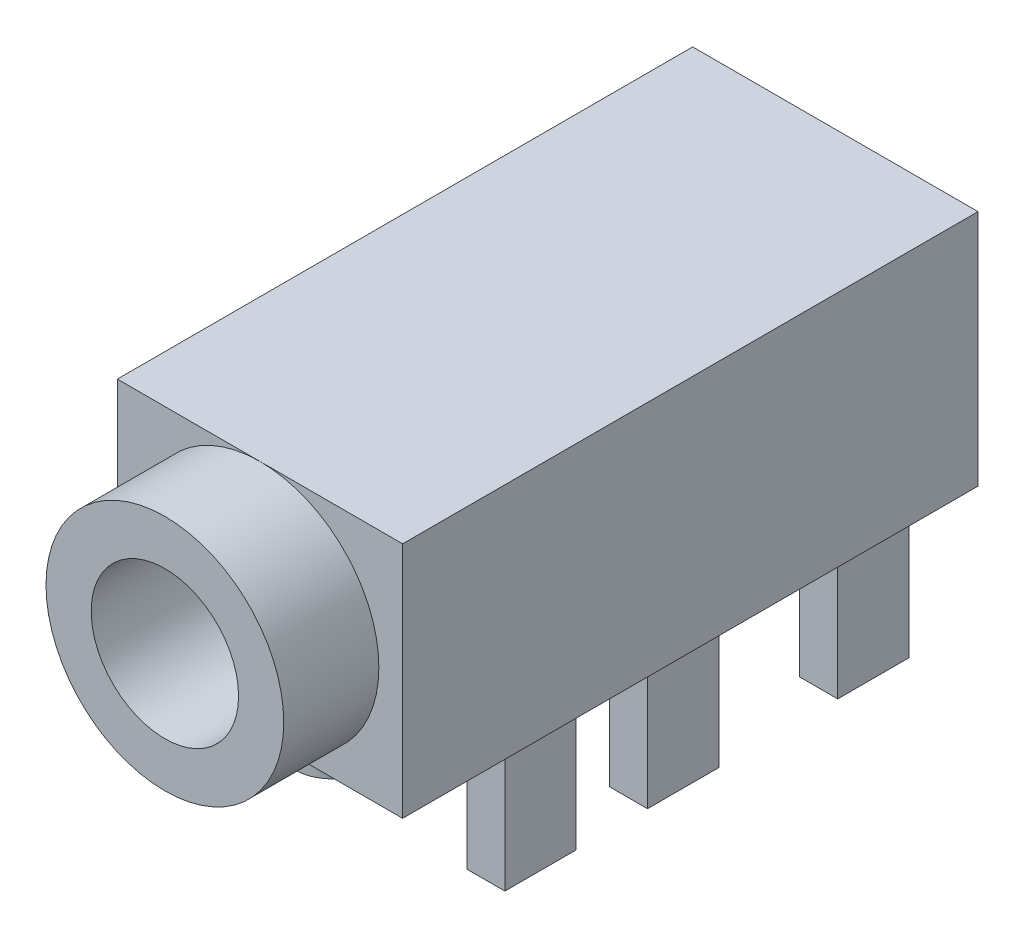
SolidWorks part; units mm, degrees
ref_plane "Front Plane" through (0, 0, 0) normal (0, 0, 1) x (1, 0, 0)
ref_plane "Top Plane" through (0, 0, 0) normal (0, 1, 0) x (1, 0, 0)
ref_plane "Right Plane" through (0, 0, 0) normal (1, 0, 0) x (0, 0, -1)
sketch "Sketch1" plane through (0, 0, 0) normal (0, 1, 0) x (1, 0, 0)
  line L1 (-3, 6.05) -> (3, 6.05)
  line L2 (-3, 6.05) -> (-3, -6.05)
  line L3 (-3, -6.05) -> (3, -6.05)
  line L4 (3, 6.05) -> (3, -6.05)
  line L5 (-3, 6.05) -> (3, -6.05) construction
  line L6 (-3, -6.05) -> (3, 6.05) construction
  point P0 (0, 0)
  dimension "D1" = 12.1
  dimension "D2" = 6
extrude "Boss-Extrude1" add sketch "Sketch1" along normal blind 5
sketch "Sketch2" plane through (0, 0, 6.05) normal (0, 0, 1) x (1, 0, 0)
  line L0 (-3, 0) -> (3, 5) construction
  circle A0 centre (0, 2.5) radius 2.5
  dimension "D1" = 5
extrude "Boss-Extrude2" add sketch "Sketch2" along normal blind 2
sketch "Sketch4" plane through (0, 0, 0) normal (0, -1, 0) x (1, 0, 0)
  line L0 (0, 6.05) -> (3, 6.05) construction
  line L1 (2.6, 3.5) -> (1.8, 3.5)
  line L2 (2.6, 3.5) -> (2.6, 2)
  line L3 (2.6, 2) -> (1.8, 2)
  line L4 (1.8, 3.5) -> (1.8, 2)
  line L5 (2.6, 3.5) -> (1.8, 2) construction
  line L6 (2.6, 2) -> (1.8, 3.5) construction
  line L7 (2.6, 0.5) -> (1.8, 0.5)
  line L8 (2.6, 0.5) -> (2.6, -1)
  line L9 (2.6, -1) -> (1.8, -1)
  line L10 (1.8, 0.5) -> (1.8, -1)
  line L11 (2.6, 0.5) -> (1.8, -1) construction
  line L12 (2.6, -1) -> (1.8, 0.5) construction
  line L13 (2.6, -3.5) -> (1.8, -3.5)
  line L14 (2.6, -3.5) -> (2.6, -5)
  line L15 (2.6, -5) -> (1.8, -5)
  line L16 (1.8, -3.5) -> (1.8, -5)
  line L17 (2.6, -3.5) -> (1.8, -5) construction
  line L18 (2.6, -5) -> (1.8, -3.5) construction
  line L19 (-1.8, -4.8) -> (-2.6, -4.8)
  line L20 (-1.8, -4.8) -> (-1.8, -6.3)
  line L21 (-1.8, -6.3) -> (-2.6, -6.3)
  line L22 (-2.6, -4.8) -> (-2.6, -6.3)
  line L23 (-1.8, -4.8) -> (-2.6, -6.3) construction
  line L24 (-1.8, -6.3) -> (-2.6, -4.8) construction
  line L25 (2.2, -4.25) -> (-2.2, -5.55) construction
  line L26 (0, -4.9) -> (0, -6.05) construction
  line L27 (3, -6.05) -> (-3, -6.05) construction
  line L28 (2.2, 2.75) -> (2.2, -4.25) construction
  point P0 (2.2, 2.75)
  point P5 (2.2, -0.25)
  point P10 (2.2, -4.25)
  point P15 (-2.2, -5.55)
  point P28 (2.0319, -3.9763)
  point P30 (0, 0)
  dimension "D1" = 1.5
  dimension "D2" = 0.8
  dimension "D3" = 1.3
  dimension "D4" = 4
  dimension "D5" = 3
  dimension "D6" = 3.3
  dimension "D7" = 4.4
extrude "Boss-Extrude3" add sketch "Sketch4" along normal blind 2.8
sketch "Sketch5" plane through (0, 0, 0) normal (0, -1, 0) x (1, 0, 0)
  line L0 (2.5, 6.05) -> (0, 6.05) construction
  circle A0 centre (0, 4.55) radius 0.75
  circle A1 centre (0, -2.45) radius 0.75
  point P4 (0, 0)
  dimension "D1" = 1.5
  dimension "D3" = 7
  dimension "D2" = 1.5
extrude "Boss-Extrude4" add sketch "Sketch5" along normal blind 1
sketch "Sketch6" plane through (0, 0, 8.05) normal (0, 0, 1) x (1, 0, 0)
  circle A0 centre (0, 2.5) radius 1.55
  circle A1 centre (0, 2.5) radius 2.5 construction
  dimension "D1" = 3.1
extrude "Cut-Extrude1" cut sketch "Sketch6" against normal blind 10
